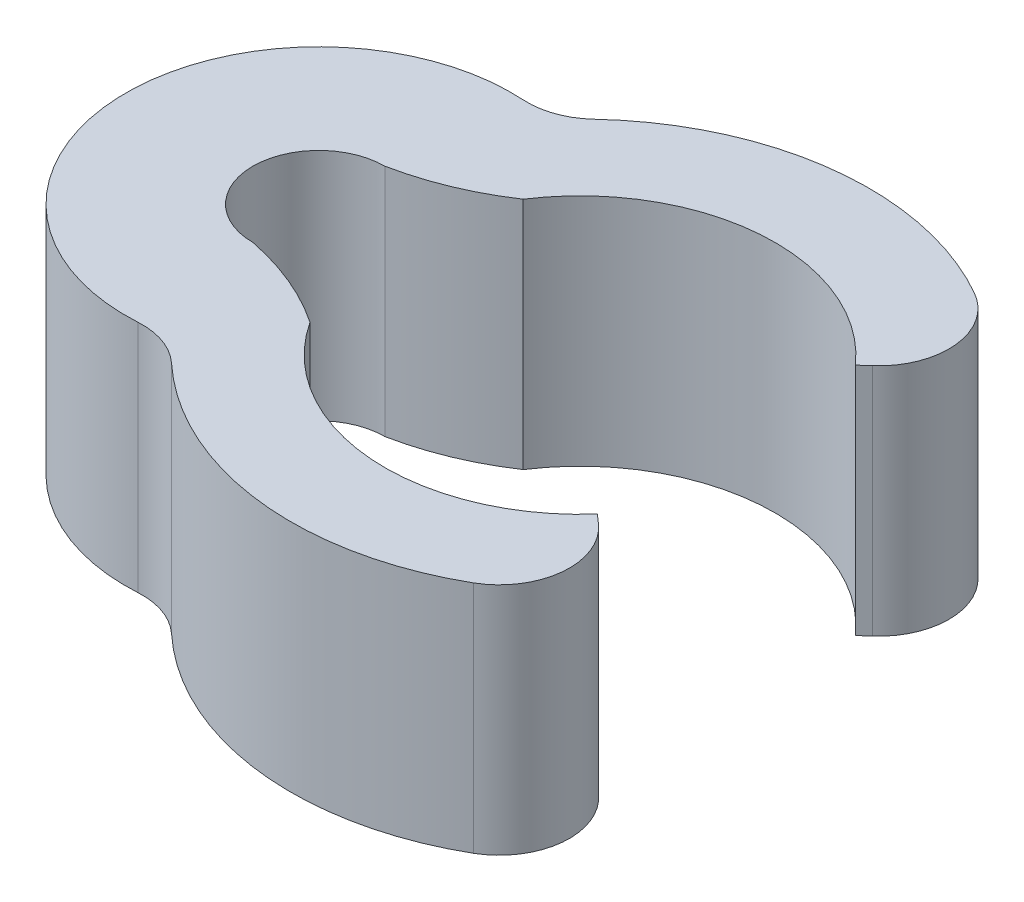
SolidWorks part; units mm, degrees
ref_plane "Front Plane" through (0, 0, 0) normal (0, 0, 1) x (1, 0, 0)
ref_plane "Top Plane" through (0, 0, 0) normal (0, 1, 0) x (1, 0, 0)
ref_plane "Right Plane" through (0, 0, 0) normal (1, 0, 0) x (0, 0, -1)
sketch "Sketch1" plane through (0, 0, 0) normal (0, 1, 0) x (1, 0, 0)
  line L0 (-80.0438, 10.1742) -> (-57.7443, 10.1742) construction
  line L1 (-66.0744, 15.6823) -> (-34.5365, 15.6823)
  line L2 (-66.0744, 18.5043) -> (-34.5365, 18.5043)
  line L3 (-66.0744, 18.5043) -> (-66.0744, 10.1742)
  line L4 (-66.0744, 10.1742) -> (-34.5365, 10.1742)
  line L5 (-34.5365, 18.5043) -> (-34.5365, 10.1742)
  line L6 (-66.0744, 10.1742) -> (-59.8253, 15.6823)
  line L7 (-59.8253, 15.6823) -> (-56.8167, 18.3342)
  line L8 (-59.8253, 4.666) -> (-56.8167, 2.0142)
  circle A1 centre (-66.0744, 10.1742) radius 8.3301
  circle A2 centre (-77.2241, 10.1742) radius 2.8196
  arc A3 (-77.2241, 12.9938) -> (-73.0513, 14.7254) centre (-79.4772, 24.3172) ccw
  arc A4 (-77.2241, 7.3545) -> (-73.0513, 5.623) centre (-79.4772, -3.9688) cw
  circle A5 centre (-66.0744, 10.1742) radius 12.3406
  circle A6 centre (-77.2241, 10.1742) radius 8.2398
  point P21 (-57.7443, 10.1742)
  point P30 (0, 0)
extrude "Boss-Extrude3" add sketch "Sketch1" along normal blind 10
fillet "Fillet3" radius 3 4 edges at (-56.8167, 5, -2.0142) (-56.8167, 5, -18.3342) (-75.434, 5, -2.1312) (-75.434, 5, -18.2171)
